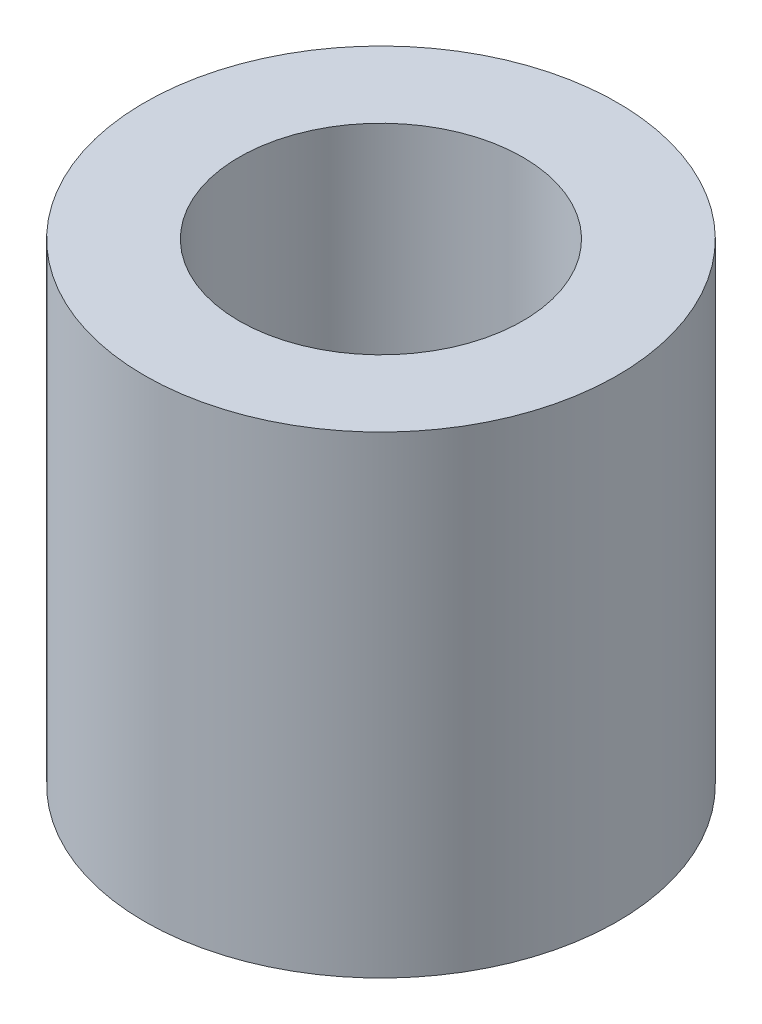
SolidWorks part; units mm, degrees
material "Brass"
ref_plane "Front Plane" through (0, 0, 0) normal (0, 0, 1) x (1, 0, 0)
ref_plane "Top Plane" through (0, 0, 0) normal (0, 1, 0) x (1, 0, 0)
ref_plane "Right Plane" through (0, 0, 0) normal (1, 0, 0) x (0, 0, -1)
sketch "Sketch1" plane through (0, 0, 0) normal (0, 1, 0) x (1, 0, 0)
  circle A0 centre (0, 0) radius 5
extrude "Boss-Extrude1" add sketch "Sketch1" along normal blind 10
shell "Shell2" thickness 2
